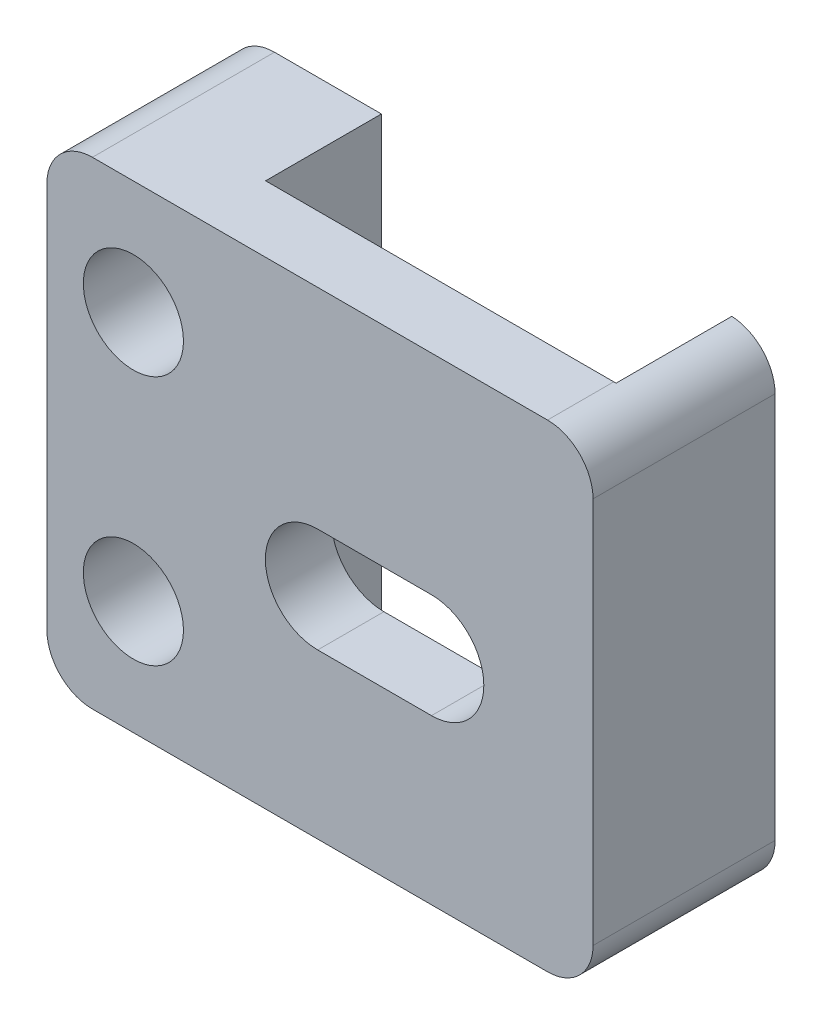
SolidWorks part; units mm, degrees
ref_plane "Front Plane" through (0, 0, 0) normal (0, 0, 1) x (1, 0, 0)
ref_plane "Top Plane" through (0, 0, 0) normal (0, 1, 0) x (1, 0, 0)
ref_plane "Right Plane" through (0, 0, 0) normal (1, 0, 0) x (0, 0, -1)
sketch "Sketch1" plane through (0, 0, 0) normal (0, 1, 0) x (1, 0, 0)
  line L1 (0, 0) -> (9.5, 0)
  line L2 (0, 0) -> (0, -4)
  line L3 (0, -4) -> (9.5, -4)
  line L4 (9.5, 0) -> (9.5, -4)
  dimension "D1" = 4
extrude "Boss-Extrude1" add sketch "Sketch1" along normal blind 10.5
sketch "Sketch2" plane through (0, 10.5, 0) normal (0, 1, 0) x (1, 0, 0)
  line L0 (0, 0) -> (0, -1.5) construction
  line L1 (0, 0) -> (0, -4) construction
  line L2 (0, -1.5) -> (1.15, -1.5) construction
  line L3 (9.5, -4) -> (9.5, 0) construction
  line L4 (9.5, -1.5) -> (9.5, 0) construction
  line L5 (9.5, -1.5) -> (8.25, -1.5) construction
  line L12 (9.5, 0) -> (0, 0) construction
  line L15 (8.25, -2.5448) -> (8.25, -1.5)
  line L17 (8.25, -2.5448) -> (1.15, -2.5448)
  line L30 (1.15, -2.5448) -> (1.15, -1.5)
  line L31 (8.25, -1.5) -> (8.25, 0)
  line L32 (8.25, 0) -> (1.15, 0)
  line L33 (1.15, -1.5) -> (1.15, 0)
  dimension "D1" = 1.5
  dimension "D2" = 1.5
  dimension "D3" = 1.25
  dimension "D4" = 1.15
extrude "Breakbeam Hole 1" cut sketch "Sketch2" against normal blind 9.5
sketch "Sketch5" plane through (0, 0, 0) normal (-1, 0, 0) x (0, 0, 1)
  line L1 (0, 0) -> (4, 0)
  line L9 (4, 10.5) -> (0, 10.5)
  line L11 (0, 10.5) -> (0, 0)
  line L12 (4, 10.5) -> (4, 0)
  dimension "D1" = 10.5
extrude "Boss-Extrude4" add sketch "Sketch5" along normal blind 2.5
fillet "Fillet1" radius 1 4 edges at (9.5, 10.5, 2) (9.5, 0, 2) (-2.5, 0, 2) (-2.5, 10.5, 2)
hole_wizard "M2 Clearance Hole" positions "Sketch12" profile "Sketch13" legacy end condition through all
sketch "Sketch12" plane through (0, 0, 4) normal (0, 0, 1) x (1, 0, 0)
  line L9 (-1.5, 0) -> (8.5, 0) construction
  line L11 (-0.6, 0) -> (-0.6, 2.5) construction
  line L13 (-2.5, 1) -> (-2.5, 9.5) construction
  line L15 (-0.6, 2.5) -> (-2.5, 2.5) construction
  line L17 (-0.6, 2.5444) -> (-0.6, 8) construction
  line L18 (-0.6, 8) -> (-0.6, 10.5) construction
  line L19 (-1.5, 10.5) -> (8.5, 10.5) construction
  point P0 (-0.6, 8)
  point P2 (-0.6, 2.5)
  dimension "D1" = 2.5
  dimension "D3" = 2.5
sketch "Sketch13" plane through (-0.6, 8, 4) normal (1, 0, 0) x (0, -1, 0)
  line L0 (0, 0) -> (0, 4)
  line L1 (0, 4) -> (1.1, 4)
  line L2 (1.1, 4) -> (1.1, 0)
  line L3 (1.1, 0) -> (0, 0)
  line L4 (0, 110) -> (0, -10) construction
  dimension "Diameter" = 2.2
  dimension "Depth" = 4
sketch "Sketch15" plane through (0, 0, 0) normal (0, 0, -1) x (-1, 0, 0)
  line L0 (-8.55, 10.8) -> (-8.55, 0.7)
  line L1 (-8.55, 0.7) -> (-0.85, 0.7)
  line L2 (-0.85, 0.7) -> (-0.85, 10.8)
  line L3 (-0.85, 10.8) -> (-8.55, 10.8)
  line L4 (-1.15, 10.5) -> (-8.25, 10.5)
  line L5 (-8.25, 10.5) -> (-8.25, 1)
  line L6 (-8.25, 1) -> (-1.15, 1)
  line L7 (-1.15, 1) -> (-1.15, 10.5)
  line L8 (-1.15, 10.5) -> (-8.25, 10.5)
  line L9 (-8.25, 10.5) -> (-8.25, 1)
  line L10 (-8.25, 1) -> (-1.15, 1)
  line L11 (-1.15, 1) -> (-1.15, 10.5)
  dimension "D1" = 0
  dimension "D2" = 0.3
extrude "Cut-Extrude5" cut sketch "Sketch15" against normal up to surface (2.5448 mm away) up to face at (4.7, 5.75, 2.5448)
sketch "Sketch16" plane through (0, 0, 4) normal (0, 0, 1) x (1, 0, 0)
  line L0 (3.45, 4.75) -> (5.95, 4.75) construction
  line L1 (3.45, 5.9) -> (5.95, 5.9)
  line L2 (3.45, 3.6) -> (5.95, 3.6)
  line L4 (-1.5, 10.5) -> (8.5, 10.5) construction
  line L5 (9.5, 9.5) -> (9.5, 1) construction
  arc A0 (3.45, 5.9) -> (3.45, 3.6) centre (3.45, 4.75) ccw
  arc A1 (5.95, 3.6) -> (5.95, 5.9) centre (5.95, 4.75) ccw
  point P2 (4.7, 4.75)
  point P11 (7.1, 4.75)
  dimension "D1" = 4.6
  dimension "D2" = 2.4
extrude "Cut-Extrude6" cut sketch "Sketch16" against normal blind 1.46
